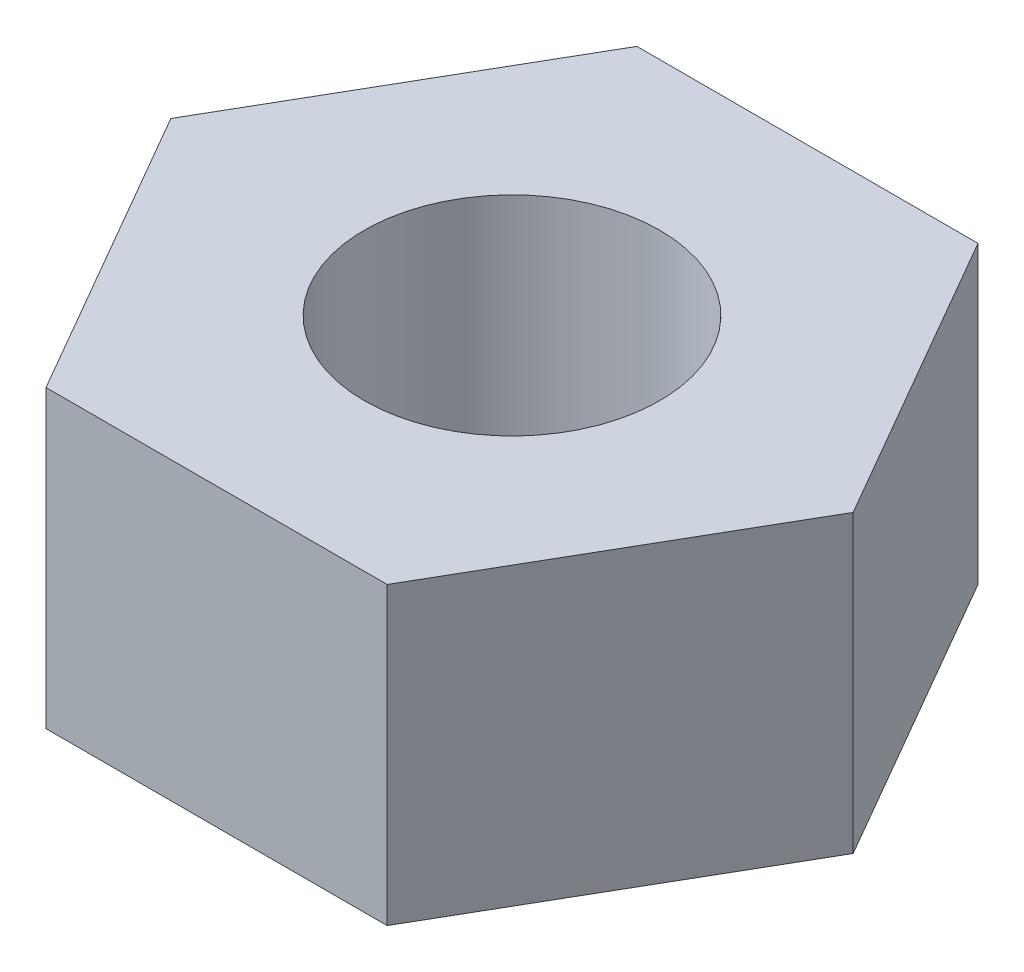
SolidWorks part; units mm, degrees
material "Cast Alloy Steel"
ref_plane "Front Plane" through (0, 0, 0) normal (0, 0, 1) x (1, 0, 0)
ref_plane "Top Plane" through (0, 0, 0) normal (0, 1, 0) x (1, 0, 0)
ref_plane "Right Plane" through (0, 0, 0) normal (1, 0, 0) x (0, 0, -1)
sketch "Sketch1" plane through (0, 0, 0) normal (0, 1, 0) x (1, 0, 0)
  line L1 (3.4641, 0) -> (1.7321, 3)
  line L2 (1.7321, 3) -> (-1.7321, 3)
  line L3 (-1.7321, 3) -> (-3.4641, 0)
  line L4 (-3.4641, 0) -> (-1.7321, -3)
  line L5 (-1.7321, -3) -> (1.7321, -3)
  line L6 (1.7321, -3) -> (3.4641, 0)
  circle A0 centre (0, 0) radius 3 construction
  circle A1 centre (0, 0) radius 1.5
  dimension "D2" = 3
  dimension "D1" = 3
extrude "Boss-Extrude1" add sketch "Sketch1" along normal blind 3
